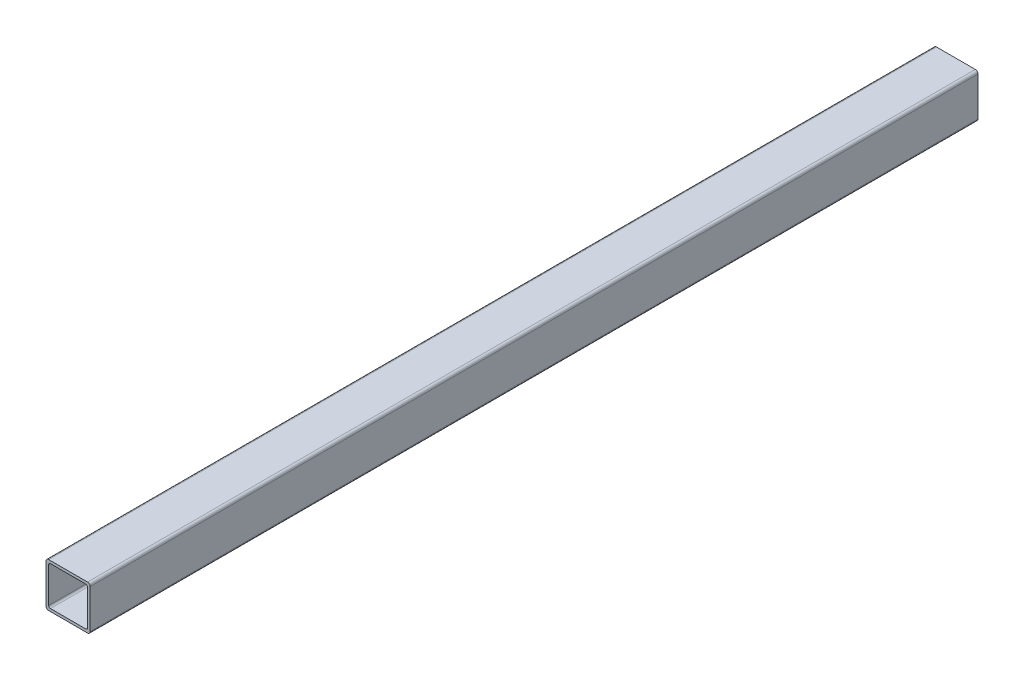
SolidWorks part; units mm, degrees
material "AISI 1020"
ref_plane "Спереди" through (0, 0, 0) normal (0, 0, 1) x (1, 0, 0)
ref_plane "Сверху" through (0, 0, 0) normal (0, 1, 0) x (1, 0, 0)
ref_plane "Справа" through (0, 0, 0) normal (1, 0, 0) x (0, 0, -1)
sketch "Эскиз1" plane through (0, 0, 0) normal (0, 0, 1) x (1, 0, 0)
  line L0 (0, -50) -> (0, 2652.4058) construction
  line L1 (-47, -50) -> (-3, -50) construction
  line B0 (-47, 0) -> (-3, 0)
  line B1 (-50, -3) -> (-50, -47)
  line B2 (-47, -50) -> (-3, -50)
  line B3 (0, -3) -> (0, -47)
  line B4 (-45, -3) -> (-5, -3)
  line B5 (-47, -5) -> (-47, -45)
  line B6 (-45, -47) -> (-5, -47)
  line B7 (-3, -5) -> (-3, -45)
  arc B8 (-50, -47) -> (-47, -50) centre (-47, -47) ccw
  arc B9 (-3, -50) -> (0, -47) centre (-3, -47) ccw
  arc B10 (-3, 0) -> (0, -3) centre (-3, -3) cw
  arc B11 (-47, 0) -> (-50, -3) centre (-47, -3) ccw
  arc B12 (-47, -45) -> (-45, -47) centre (-45, -45) ccw
  arc B13 (-5, -47) -> (-3, -45) centre (-5, -45) ccw
  arc B14 (-5, -3) -> (-3, -5) centre (-5, -5) cw
  arc B15 (-45, -3) -> (-47, -5) centre (-45, -5) ccw
sketch_block_instance "Труба профильная 50х50х3-1"
sketch_block "Труба профильная 50х50х3" parameters "D3"=3, "D4"=2, "D1"=50, "D2"=3
extrude "Бобышка-Вытянуть1" add sketch "Эскиз1" against normal up to surface (1005 mm away)
